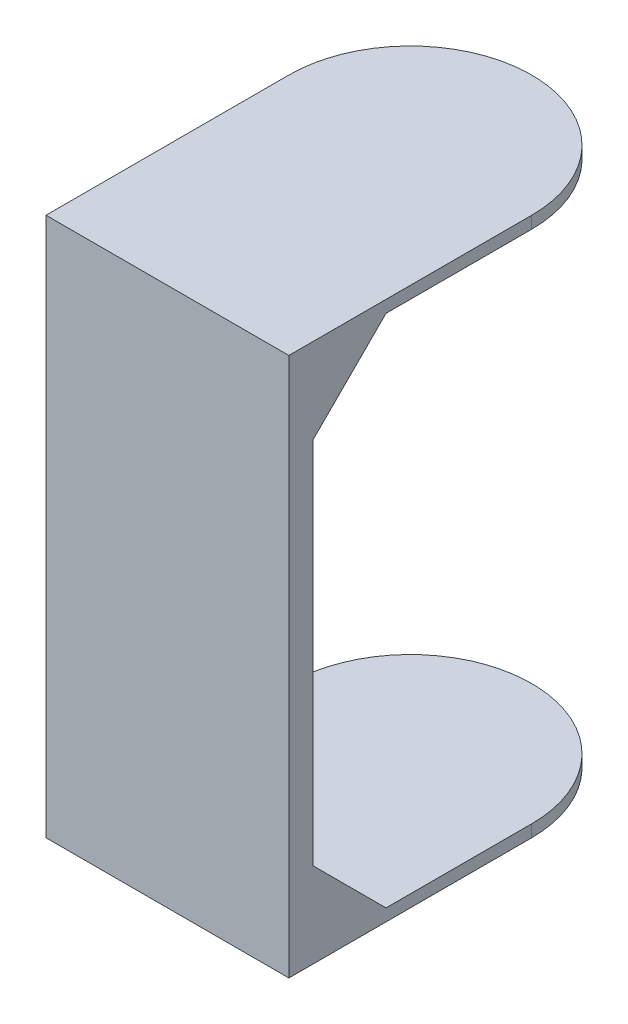
SolidWorks part; units mm, degrees
ref_plane "Front Plane" through (0, 0, 0) normal (0, 0, 1) x (1, 0, 0)
ref_plane "Top Plane" through (0, 0, 0) normal (0, 1, 0) x (1, 0, 0)
ref_plane "Right Plane" through (0, 0, 0) normal (1, 0, 0) x (0, 0, -1)
sketch "Plate Sketch" plane through (0, 0, 0) normal (0, 0, 1) x (1, 0, 0)
  line L1 (-50, 106) -> (50, 106)
  line L2 (-50, 106) -> (-50, -106)
  line L3 (-50, -106) -> (50, -106)
  line L4 (50, 106) -> (50, -106)
  line L5 (-50, 106) -> (50, -106) construction
  line L6 (-50, -106) -> (50, 106) construction
  point P0 (0, 0)
  dimension "D1" = 100
  dimension "D2" = 212
extrude "Plate Extrude" add sketch "Plate Sketch" against normal blind 10
sketch "Primary Support Sketch" plane through (50, 0, 0) normal (1, 0, 0) x (0, 0, -1)
  line L0 (10, 106) -> (10, 76)
  line L1 (10, 76) -> (40, 106)
  line L2 (40, 106) -> (10, 106)
  dimension "D1" = 30
extrude "Primary Support Extrude" add sketch "Primary Support Sketch" against normal blind 10
mirror "Primary Support Mirror" about plane through (0, 0, 0) normal (0, 1, 0) of "Primary Support Extrude"
sketch "Secondary Support Sketch" plane through (-50, 0, 0) normal (-1, 0, 0) x (0, 0, 1)
  line L0 (-10, 76) -> (-40, 106)
  line L3 (-40, 106) -> (-10, 106)
  line L4 (-10, 106) -> (-10, 76)
extrude "Secondary Support Extrude" add sketch "Secondary Support Sketch" against normal blind 10
sketch "Gripper Sketch" plane through (0, 106, 0) normal (0, 1, 0) x (1, 0, 0)
  line L0 (50, 100) -> (-50, 100) construction
  line L1 (0, 150) -> (0, 0) construction
  line L7 (-50, 0) -> (50, 0)
  line L8 (-50, 0) -> (-50, 100)
  line L9 (-50, 100) -> (50, 100) construction
  line L10 (50, 0) -> (50, 100)
  line L11 (-50, 0) -> (50, 100) construction
  line L12 (-50, 100) -> (50, 0) construction
  arc A0 (50, 100) -> (-50, 100) centre (0, 100) ccw
  point P5 (0, 150)
  point P6 (0, 50)
extrude "Gripper Extrude" add sketch "Gripper Sketch" along normal blind 5
mirror "Gripper Mirror" about plane through (0, 0, 0) normal (0, 1, 0) of "Gripper Extrude"
